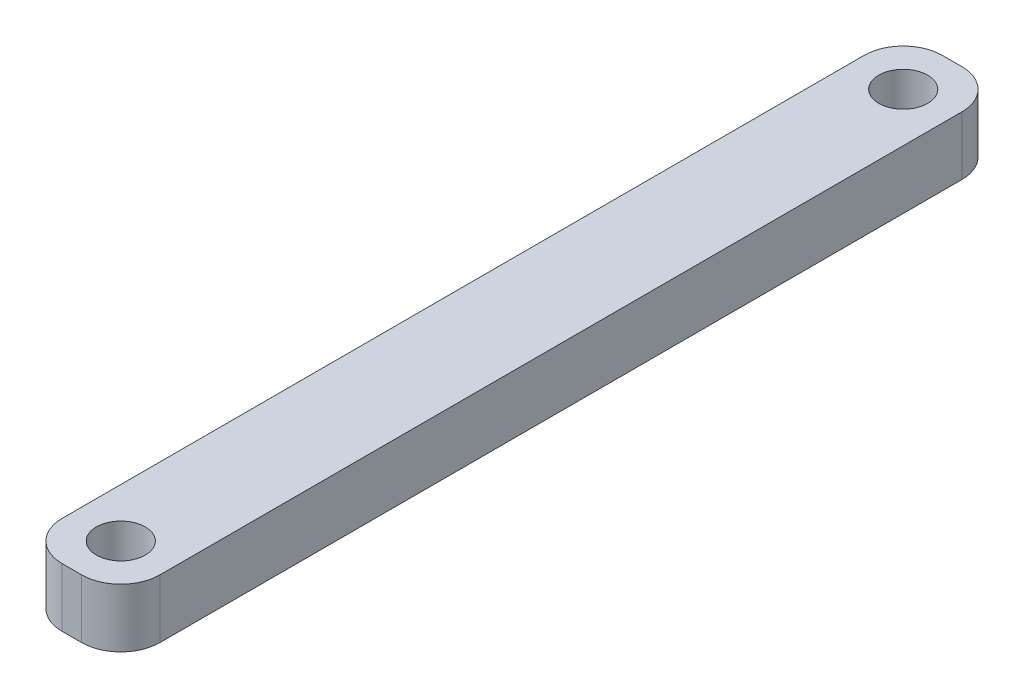
SolidWorks part; units mm, degrees
ref_plane "Front Plane" through (0, 0, 0) normal (0, 0, 1) x (1, 0, 0)
ref_plane "Top Plane" through (0, 0, 0) normal (0, 1, 0) x (1, 0, 0)
ref_plane "Right Plane" through (0, 0, 0) normal (1, 0, 0) x (0, 0, -1)
sketch "Sketch1" plane through (0, 0, 0) normal (0, 1, 0) x (1, 0, 0)
  line L0 (0, 0) -> (2.5, 0) construction
  line L1 (-2.5, -22.5) -> (2.5, -22.5)
  line L2 (-2.5, -22.5) -> (-2.5, 22.5)
  line L3 (-2.5, 22.5) -> (2.5, 22.5)
  line L4 (2.5, -22.5) -> (2.5, 22.5)
  line L5 (-2.5, -22.5) -> (2.5, 22.5) construction
  line L6 (-2.5, 22.5) -> (2.5, -22.5) construction
  line L7 (0, 0) -> (0, 22.5) construction
  circle A0 centre (0, 20) radius 1.25
  circle A1 centre (0, -20) radius 1.25
  point P0 (0, 0)
  dimension "D3" = 40
  dimension "D4" = 2.5
  dimension "D1" = 45
  dimension "D2" = 5
extrude "Boss-Extrude1" add sketch "Sketch1" along normal blind 3
fillet "Fillet1" radius 2 4 edges at (-2.5, 1.5, 22.5) (2.5, 1.5, 22.5) (2.5, 1.5, -22.5) (-2.5, 1.5, -22.5)
